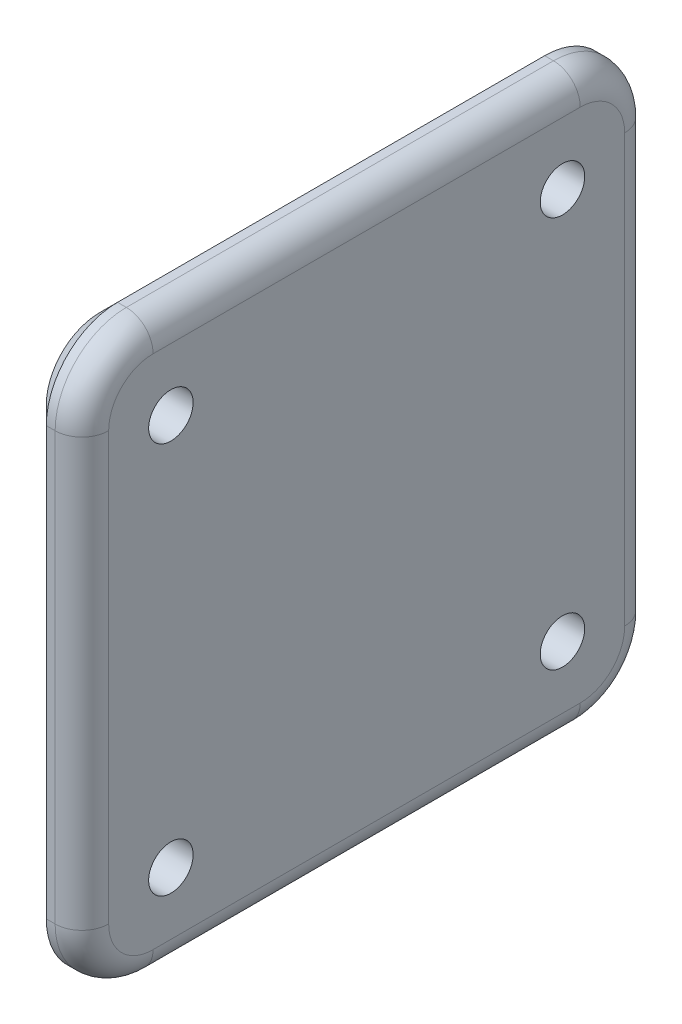
SolidWorks part; units mm, degrees
ref_plane "front" through (0, 0, 0) normal (0, 0, 1) x (1, 0, 0)
ref_plane "top" through (0, 0, 0) normal (0, 1, 0) x (1, 0, 0)
ref_plane "right" through (0, 0, 0) normal (1, 0, 0) x (0, 0, -1)
sketch "Sketch1" plane through (0, 0, 0) normal (1, 0, 0) x (0, 0, -1)
  line L0 (-127, 127) -> (-50.8, 50.8) construction
  line L1 (-127, 139.7) -> (-50.8, 139.7)
  line L2 (-139.7, 127) -> (-139.7, 50.8)
  line L3 (-127, 38.1) -> (-50.8, 38.1)
  line L4 (-38.1, 127) -> (-38.1, 50.8)
  arc A0 (-38.1, 50.8) -> (-50.8, 38.1) centre (-50.8, 50.8) cw
  arc A1 (-127, 38.1) -> (-139.7, 50.8) centre (-127, 50.8) cw
  arc A2 (-127, 139.7) -> (-139.7, 127) centre (-127, 127) ccw
  arc A3 (-38.1, 127) -> (-50.8, 139.7) centre (-50.8, 127) ccw
  point P12 (-88.9, 88.9)
  dimension "D3" = 12.7
  dimension "D1" = 101.6
  dimension "D2" = 101.6
  dimension "D4" = 88.9
  dimension "D5" = 88.9
extrude "Base-Extrude" add sketch "Sketch1" along normal blind 9.525
chamfer "Chamfer1" distance 3.175 angle 45 8 edges at (0, 38.1, 88.9) (0, 41.8197, 135.9803) (0, 88.9, 139.7) (0, 135.9803, 135.9803) (0, 139.7, 88.9) (0, 135.9803, 41.8197) (0, 88.9, 38.1) (0, 41.8197, 41.8197)
fillet "Fillet1" radius 4.7752 8 edges at (9.525, 135.9803, 41.8197) (9.525, 139.7, 88.9) (9.525, 135.9803, 135.9803) (9.525, 88.9, 139.7) (9.525, 41.8197, 135.9803) (9.525, 38.1, 88.9) (9.525, 41.8197, 41.8197) (9.525, 88.9, 38.1)
sketch "Sketch2" plane through (9.525, 0, 0) normal (1, 0, 0) x (0, 0, -1)
  line L0 (-50.8, 38.1) -> (-127, 38.1) construction
  line L1 (-38.1, 127) -> (-38.1, 50.8) construction
  circle A0 centre (-53.975, 53.975) radius 3.9687
  circle A1 centre (-53.975, 123.825) radius 3.9687
  circle A2 centre (-123.825, 123.825) radius 3.9687
  circle A3 centre (-123.825, 53.975) radius 3.9687
  dimension "D1" = 7.9375
  dimension "D2" = 15.875
  dimension "D3" = 69.85
  dimension "D4" = 69.85
  dimension "D5" = 15.875
extrude "Cut-Extrude1" cut sketch "Sketch2" against normal blind 25.4
